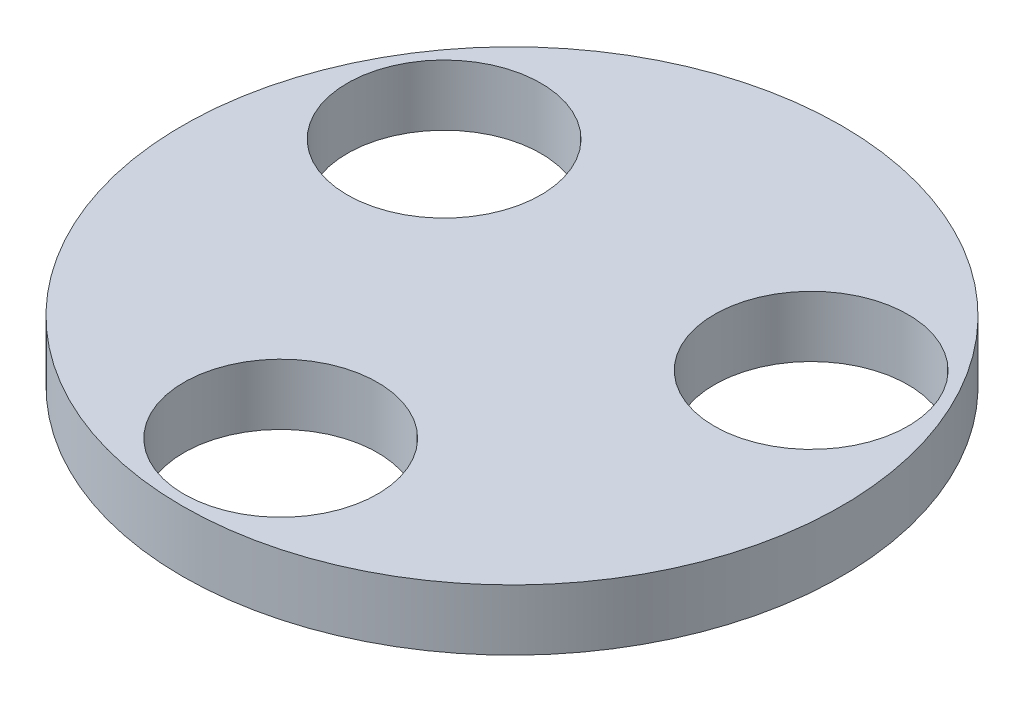
SolidWorks part; units mm, degrees
ref_plane "Front Plane" through (0, 0, 0) normal (0, 0, 1) x (1, 0, 0)
ref_plane "Top Plane" through (0, 0, 0) normal (0, 1, 0) x (1, 0, 0)
ref_plane "Right Plane" through (0, 0, 0) normal (1, 0, 0) x (0, 0, -1)
sketch "Sketch3" plane through (0, 0, 0) normal (0, 1, 0) x (1, 0, 0)
  circle A0 centre (0, 0) radius 32.5
  dimension "D1" = 65
extrude "Boss-Extrude1" add sketch "Sketch3" along normal blind 6
sketch "Sketch7" plane through (0, 6, 0) normal (0, 1, 0) x (1, 0, 0)
  line L0 (0, 0) -> (32.5, 0) construction
  line L1 (0, 0) -> (-17.3949, 11.0818) construction
  line L2 (0, 0) -> (-0.9542, -21.8542) construction
  circle A0 centre (0, 0) radius 32.5 construction
  circle A8 centre (-0.9542, -21.8542) radius 9.55
  circle A9 centre (-18.4492, 11.7534) radius 9.55
  circle A10 centre (19.4034, 10.1008) radius 9.55
  point P17 (0, 0)
  dimension "D4" = 3
  dimension "D3" = 19.1
  dimension "D2" = 120
extrude "Cut-Extrude1" cut sketch "Sketch7" against normal blind 10
